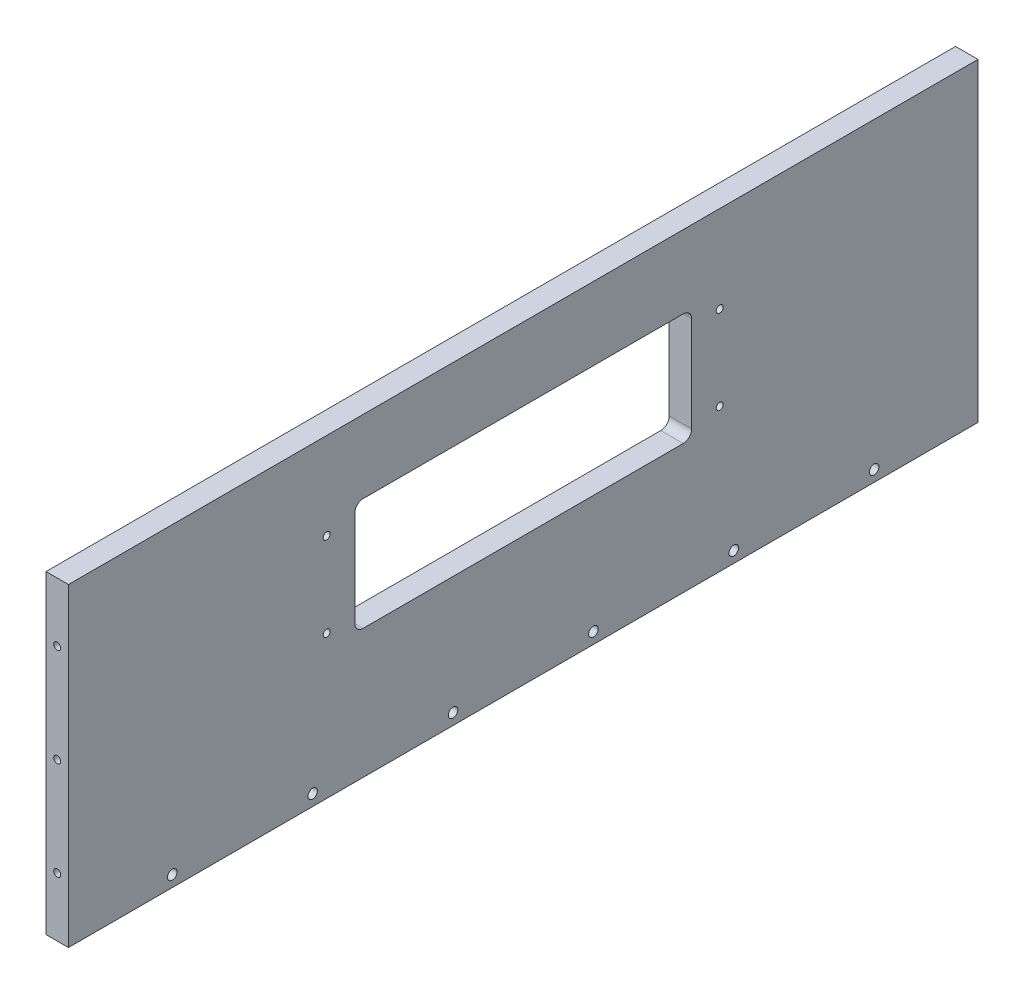
SolidWorks part; units mm, degrees
ref_plane "Front Plane" through (0, 0, 0) normal (0, 0, 1) x (1, 0, 0)
ref_plane "Top Plane" through (0, 0, 0) normal (0, 1, 0) x (1, 0, 0)
ref_plane "Right Plane" through (0, 0, 0) normal (1, 0, 0) x (0, 0, -1)
sketch "Sketch1" plane through (0, 0, 0) normal (1, 0, 0) x (0, 0, -1)
  line L1 (162, -56) -> (-162, -56)
  line L2 (162, -56) -> (162, 56)
  line L3 (162, 56) -> (-162, 56)
  line L4 (-162, -56) -> (-162, 56)
  line L5 (162, -56) -> (-162, 56) construction
  line L6 (162, 56) -> (-162, -56) construction
  point P0 (0, 0)
  dimension "D1" = 324
  dimension "D2" = 112
extrude "Boss-Extrude1" add sketch "Sketch1" along normal blind 8
sketch "Sketch2" plane through (0, 0, 162) normal (0, 0, 1) x (1, 0, 0)
  point P0 (4, -35)
  point P2 (4, 0)
  point P4 (4, 35)
hole_wizard "M3x0.5 Tapped Hole1" positions "3DSketch1" profile "Sketch4" tap size "M3x0.5" standard "BSI"
sketch3d "3DSketch1"
  point P0 (4, 35, 162)
  point P3 (4, 0, 162)
  point P6 (4, -35, 162)
sketch "Sketch4" plane through (4, 35, 162) normal (1, 0, 0) x (0, -1, 0)
  line L0 (0, 0) -> (0, 12.2511)
  line L1 (0, 12.2511) -> (1.25, 11.5)
  line L2 (1.25, 11.5) -> (1.25, 0)
  line L5 (1.25, 0) -> (0, 0)
  line L10 (0, 12.2511) -> (-1.25, 11.5) construction
  line L11 (0, -6.35) -> (0, 107.95) construction
  dimension "Tap Drill Dia." = 2.5
  dimension "Tap Drill Depth" = 11.5
  dimension "Drill Angle" = 118
cosmetic thread "Hole Thread1" parameters "D1"=10, "D2"=3
cosmetic thread "Hole Thread2" parameters "D1"=10, "D2"=3
cosmetic thread "Hole Thread3" parameters "D1"=10, "D2"=3
mirror "Mirror1" about plane through (0, 0, 0) normal (0, 0, 1) of "M3x0.5 Tapped Hole1"
sketch "Sketch5" plane through (0, 0, 0) normal (-1, 0, 0) x (0, 0, 1)
  line L0 (-162, -52) -> (162, -52) construction
  line L1 (-162, -56) -> (-162, 56) construction
  line L2 (162, 56) -> (162, -56) construction
  line L3 (162, -56) -> (-162, -56) construction
  line L4 (0, -52) -> (0, -56) construction
  point P8 (-125, -52)
  point P9 (-25, -52)
  point P12 (-75, -52)
  point P13 (25, -52)
  point P14 (75, -52)
  point P17 (125, -52)
  dimension "D1" = 4
  dimension "D2" = 50
  dimension "D3" = 25
  dimension "D4" = 50
hole_wizard "CSK for M3 Countersunk Flat Head1" positions "3DSketch2" profile "Sketch7" countersink size "M3" standard "BSI"
sketch3d "3DSketch2"
  point P0 (0, -52, -125)
  point P3 (0, -52, -75)
  point P6 (0, -52, -25)
  point P9 (0, -52, 25)
  point P12 (0, -52, 75)
  point P15 (0, -52, 125)
sketch "Sketch7" plane through (0, -52, -125) normal (0, 1, 0) x (0, 0, 1)
  line L0 (0, 0) -> (0, 12.5215)
  line L1 (0, 12.5215) -> (1.7, 11.5)
  line L2 (1.7, 11.5) -> (1.7, 1.45)
  line L3 (1.7, 1.45) -> (3.15, 0)
  line L5 (3.15, 0) -> (0, 0)
  line L6 (-1.7, 1.45) -> (-3.15, 0) construction
  line L10 (0, 12.5215) -> (-1.7, 11.5) construction
  line L11 (0, -6.35) -> (0, 107.95) construction
  dimension "Hole Dia." = 3.4
  dimension "Hole Depth" = 11.5
  dimension "Near C'Sink Dia." = 6.3
  dimension "Near C'Sink Angle" = 90
  dimension "Drill Angle" = 118
sketch "Sketch8" plane through (8, 0, 0) normal (1, 0, 0) x (0, 0, -1)
  line L0 (0, -56) -> (0, 4) construction
  line L1 (-162, -56) -> (162, -56) construction
  line L2 (0, 4) -> (65, 4) construction
  point P7 (65, 4)
  dimension "D1" = 60
  dimension "D2" = 130
sketch "Sketch9" plane through (0, 0, 0) normal (-1, 0, 0) x (0, 0, 1)
  line L1 (60, -10) -> (-60, -10)
  line L2 (60, -10) -> (60, 30)
  line L3 (60, 30) -> (-60, 30)
  line L4 (-60, -10) -> (-60, 30)
  line L5 (60, -10) -> (-60, 30) construction
  line L6 (60, 30) -> (-60, -10) construction
  point P0 (0, 10)
  point P6 (0, 22.8484)
  point P8 (0, 0)
  dimension "D1" = 120
  dimension "D2" = 40
  dimension "D3" = 10
extrude "Cut-Extrude1" cut sketch "Sketch9" against normal through all
sketch "Sketch10" plane through (0, 0, 0) normal (-1, 0, 0) x (0, 0, 1)
  line L0 (-60, -10) -> (60, -10) construction
  line L1 (60, 30) -> (-60, 30) construction
  line L2 (-60, 30) -> (-60, -10) construction
  point P0 (-70, 25)
  point P1 (-70, -5)
  point P8 (0, 0)
  dimension "D1" = 5
  dimension "D2" = 5
  dimension "D3" = 10
hole_wizard "M3x0.5 Tapped Hole2" positions "3DSketch3" profile "Sketch11" tap size "M3x0.5" standard "ANSI Metric" end condition through all
sketch3d "3DSketch3"
  point P0 (0, 25, -70)
  point P3 (0, -5, -70)
sketch "Sketch11" plane through (0, 25, -70) normal (0, 1, 0) x (0, 0, 1)
  line L0 (0, 0) -> (0, 8)
  line L1 (0, 8) -> (1.25, 8)
  line L2 (1.25, 8) -> (1.25, 0)
  line L5 (1.25, 0) -> (0, 0)
  line L11 (0, -6.35) -> (0, 107.95) construction
  dimension "Thru Tap Drill Dia." = 2.5
  dimension "Thru Tap Drill Depth" = 8
cosmetic thread "Hole Thread4" parameters "D2"=3
cosmetic thread "Hole Thread5" parameters "D2"=3
mirror "Mirror2" about plane through (0, 0, 0) normal (0, 0, 1) of "M3x0.5 Tapped Hole2"
fillet "Fillet1" radius 3 4 edges at (4, -10, -60) (4, -10, 60) (4, 30, 60) (4, 30, -60)
equation "\"D3@Sketch5\"=\"D4@Sketch5\"/2"
equation "\"D2@Sketch5\"=\"D4@Sketch5\""
